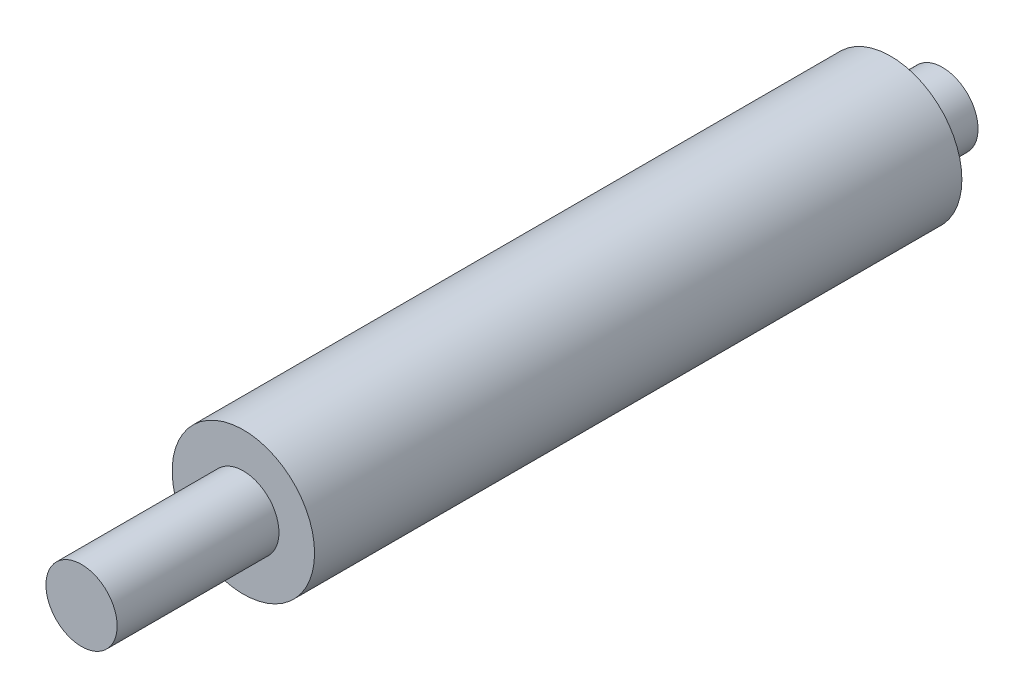
SolidWorks part; units mm, degrees
ref_plane "Front Plane" through (0, 0, 0) normal (0, 0, 1) x (1, 0, 0)
ref_plane "Top Plane" through (0, 0, 0) normal (0, 1, 0) x (1, 0, 0)
ref_plane "Right Plane" through (0, 0, 0) normal (1, 0, 0) x (0, 0, -1)
sketch "Sketch2" plane through (0, 0, 0) normal (0, 0, 1) x (1, 0, 0)
  circle A0 centre (0, 0) radius 2.2
  dimension "D1" = 4.4
extrude "Boss-Extrude1" add sketch "Sketch2" along normal blind 20
sketch "Sketch3" plane through (0, 0, 20) normal (0, 0, 1) x (1, 0, 0)
  circle A0 centre (0, 0) radius 1.1
  dimension "D1" = 2.2
extrude "Boss-Extrude2" add sketch "Sketch3" along normal blind 5
sketch "Sketch4" plane through (0, 0, 0) normal (0, 0, -1) x (-1, 0, 0)
  circle A0 centre (0, 0) radius 1.1
  dimension "D1" = 2.2
extrude "Boss-Extrude3" add sketch "Sketch4" along normal blind 1.6
